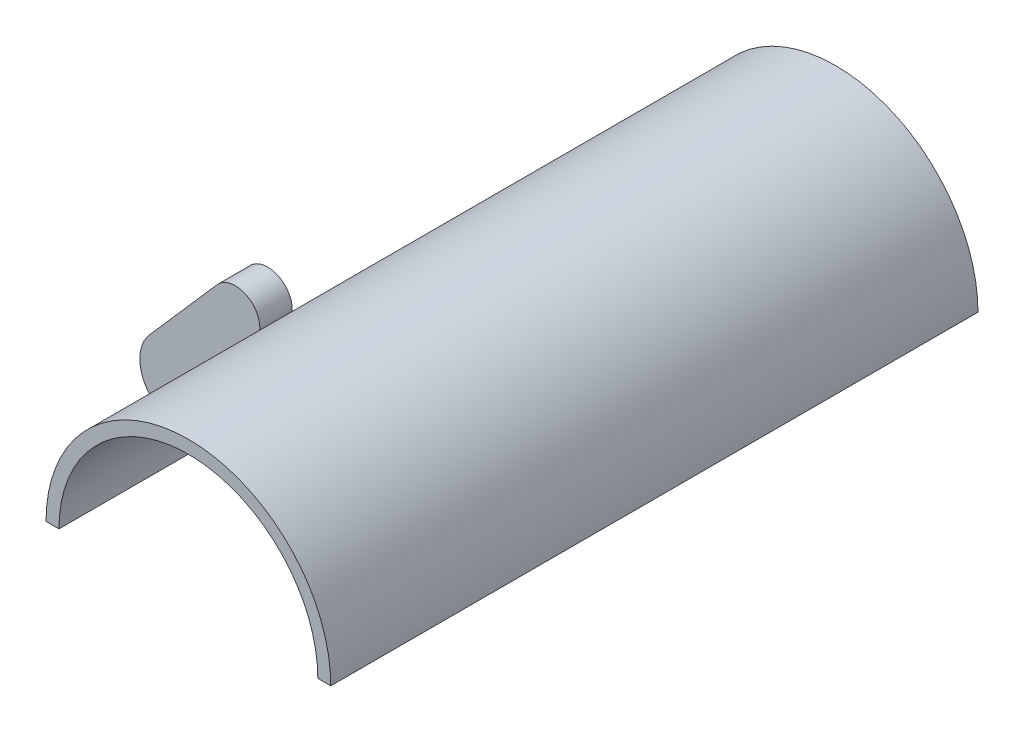
SolidWorks part; units mm, degrees
ref_plane "前视基准面" through (0, 0, 0) normal (0, 0, 1) x (1, 0, 0)
ref_plane "上视基准面" through (0, 0, 0) normal (0, 1, 0) x (1, 0, 0)
ref_plane "右视基准面" through (0, 0, 0) normal (1, 0, 0) x (0, 0, -1)
sketch "草图1" plane through (0, 0, 0) normal (0, 0, 1) x (1, 0, 0)
  line L0 (-22, 0) -> (22, 0) construction
  line L1 (-22, 0) -> (-20, 0)
  line L2 (22, 0) -> (20, 0)
  arc A0 (22, 0) -> (-22, 0) centre (0, 0) ccw
  arc A1 (20, 0) -> (-20, 0) centre (0, 0) ccw
  dimension "D1" = 40
  dimension "D2" = 44
extrude "凸台-拉伸1" add sketch "草图1" along normal mid plane 100
ref_plane "基准面1" through (0, 0, 21) normal (0, 0, 1) x (1, 0, 0)
sketch "草图2" plane through (0, 0, 21) normal (0, 0, 1) x (1, 0, 0)
  line L0 (-35.0165, 3.9499) -> (-24.5856, 15.877)
  line L2 (-24.9918, -2.379) -> (-20.1967, 8.7231)
  line L4 (-23.6968, 14.9488) -> (-33.6276, 2.4937)
  line L5 (-26.9619, -1.866) -> (-19.5308, 12.224)
  arc A0 (-33.6276, 2.4937) -> (-26.9619, -1.866) centre (-30.5, 0) ccw
  arc A1 (-18.0543, 12.5715) -> (-20.1967, 8.7231) centre (0, 0) ccw
  arc A2 (-35.0165, 3.9499) -> (-24.9918, -2.379) centre (-30.5, 0) ccw
  arc A4 (-19.5308, 12.224) -> (-23.6968, 14.9488) centre (-21.7421, 13.3902) ccw
  arc A5 (-18.0543, 12.5715) -> (-20.1967, 8.7231) centre (0, 0) ccw
  arc A6 (-18.0543, 12.5715) -> (-24.5856, 15.877) centre (-21.7421, 13.3902) ccw
  arc A7 (22, 0) -> (-22, 0) centre (0, 0) ccw construction
  dimension "D2" = 8
  dimension "D3" = 12
  dimension "D4" = 5
  dimension "D5" = 21.7421
  dimension "D1" = 30.5
  dimension "D6" = 13.3902
extrude "凸台-拉伸3" add sketch "草图2" against normal blind 5
sketch "草图3" plane through (0, 0, 21) normal (0, 0, 1) x (1, 0, 0)
  line L0 (-23.6968, 14.9488) -> (-33.6276, 2.4937) construction
  line L1 (-26.9619, -1.866) -> (-19.5308, 12.224) construction
  line L2 (-23.6968, 14.9488) -> (-33.6276, 2.4937)
  line L3 (-26.9619, -1.866) -> (-19.5308, 12.224)
  arc A0 (-19.5308, 12.224) -> (-23.6968, 14.9488) centre (-21.7421, 13.3902) ccw construction
  arc A1 (-33.6276, 2.4937) -> (-26.9619, -1.866) centre (-30.5, 0) ccw construction
  arc A2 (-19.5308, 12.224) -> (-23.6968, 14.9488) centre (-21.7421, 13.3902) ccw
  arc A3 (-33.6276, 2.4937) -> (-26.9619, -1.866) centre (-30.5, 0) ccw
extrude "凸台-拉伸4" add sketch "草图3" against normal blind 1
ref_plane "基准面2" through (0, 0, 18.5) normal (0, 0, -1) x (-1, 0, 0)
ref_plane "基准面3" through (0, 0, -18) normal (0, 0, -1) x (-1, 0, 0)
sketch "草图6" plane through (0, 0, -18) normal (0, 0, -1) x (-1, 0, 0)
  line L0 (20, 0) -> (22, 0)
  line L1 (18.1262, 8.4524) -> (19.9388, 9.2976)
  arc A0 (20, 0) -> (18.1262, 8.4524) centre (0, 0) ccw
  arc A2 (22, 0) -> (19.9388, 9.2976) centre (0, 0) ccw
  arc A3 (20, 0) -> (-20, 0) centre (0, 0) ccw construction
  dimension "D1" = 25
extrude "切除-拉伸2" cut sketch "草图6" against normal blind 27
ref_plane "基准面4" through (0, 0, 18.5) normal (0, 0, 1) x (1, 0, 0)
sketch "草图8" plane through (0, 0, 18.5) normal (0, 0, 1) x (1, 0, 0)
  line L0 (-24.9918, -2.379) -> (-22, 0)
rib "筋1" sketch "草图8" sketch "草图8" thickness 5 extrusion direction parallel to sketch draft on no parameters "D1"=5
